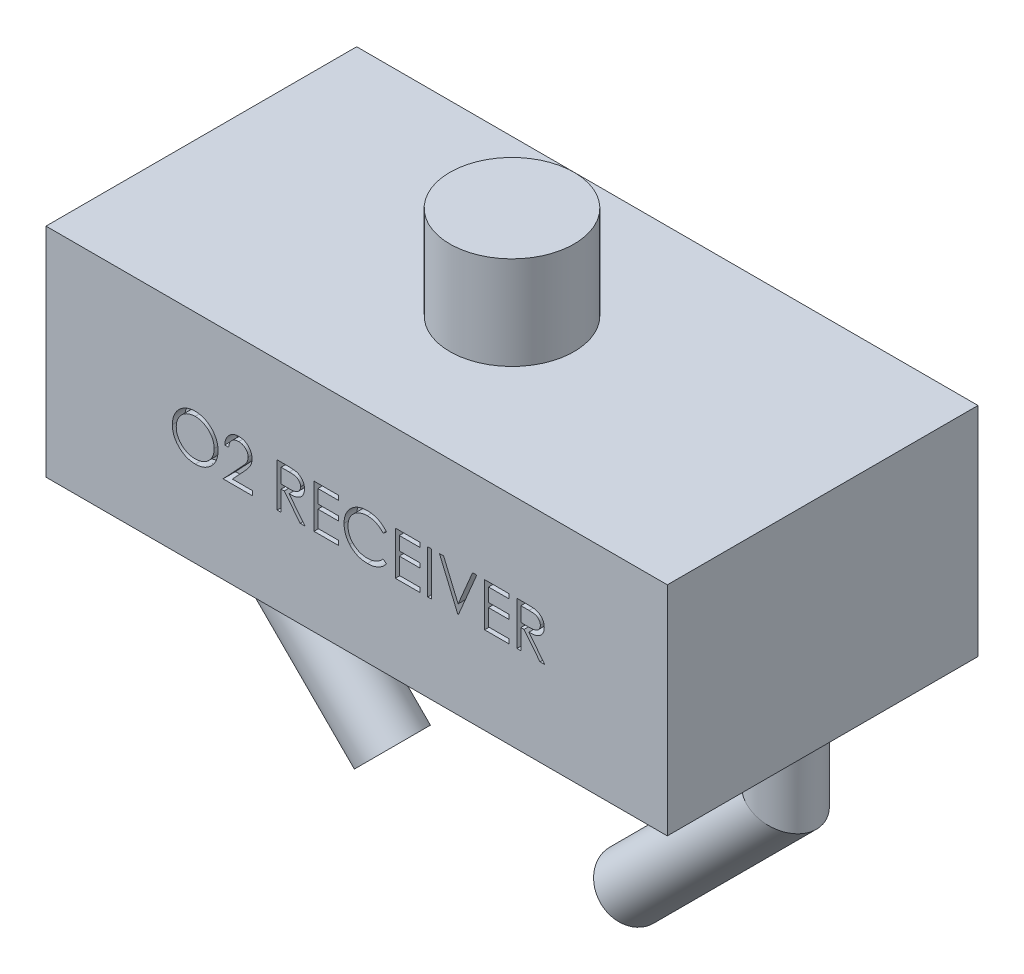
SolidWorks part; units mm, degrees
ref_plane "Front Plane" through (0, 0, 0) normal (0, 0, 1) x (1, 0, 0)
ref_plane "Top Plane" through (0, 0, 0) normal (0, 1, 0) x (1, 0, 0)
ref_plane "Right Plane" through (0, 0, 0) normal (1, 0, 0) x (0, 0, -1)
sketch "Sketch1" plane through (0, 0, 0) normal (0, 0, 1) x (1, 0, 0)
  line L1 (25, -8.75) -> (-25, -8.75)
  line L2 (25, -8.75) -> (25, 8.75)
  line L3 (25, 8.75) -> (-25, 8.75)
  line L4 (-25, -8.75) -> (-25, 8.75)
  line L5 (25, -8.75) -> (-25, 8.75) construction
  line L6 (25, 8.75) -> (-25, -8.75) construction
  point P0 (0, 0)
  dimension "D1" = 50
  dimension "D2" = 17.5
extrude "Boss-Extrude1" add sketch "Sketch1" along normal mid plane 25
sketch "Sketch2" plane through (0, 0, 12.5) normal (0, 0, 1) x (1, 0, 0)
  line L0 (-19.1501, -1.7386) -> (19.4569, -1.7386) construction
  text T0 "O2 RECEIVER"
extrude "Cut-Extrude1" cut sketch "Sketch2" against normal blind 1
sketch "Sketch3" plane through (0, 8.75, 0) normal (0, 1, 0) x (1, 0, 0)
  circle A0 centre (0, 0) radius 5
  dimension "D1" = 10
extrude "Boss-Extrude2" add sketch "Sketch3" along normal blind 7.5
sketch "Sketch4" plane through (0, 0, 0) normal (0, 0, 1) x (1, 0, 0)
  line L0 (-22, -8.75) -> (-22, -13.75)
  line L1 (-25, -8.75) -> (25, -8.75) construction
  line L2 (-22, -13.75) -> (-9.6256, -26.1244)
  line L3 (-25, 8.75) -> (-25, -8.75) construction
  point P4 (-22.9088, -13.75)
  dimension "D1" = 5
  dimension "D2" = 135
  dimension "D3" = 3
  dimension "D4" = 17.5
sketch "Sketch5" plane through (0, -8.75, 0) normal (0, -1, 0) x (1, 0, 0)
  circle A0 centre (-22, 0) radius 2.5
  point P3 (-22.9088, 0)
  dimension "D1" = 5
sweep "Sweep1" add profiles "Sketch5" path "Sketch4"
mirror "Mirror1" about plane through (0, 0, 0) normal (1, 0, 0) of "Sweep1"
